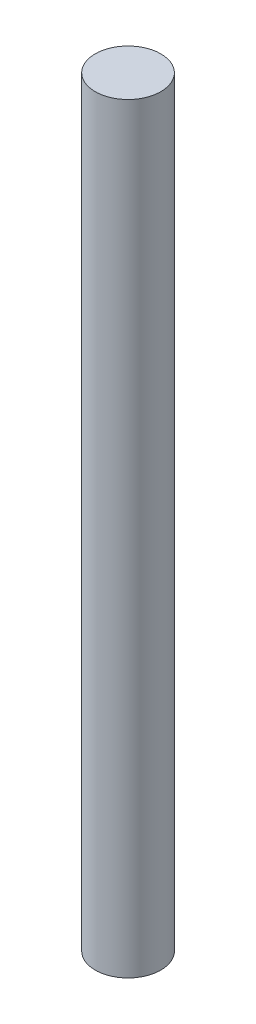
SolidWorks part; units mm, degrees
ref_plane "Front Plane" through (0, 0, 0) normal (0, 0, 1) x (1, 0, 0)
ref_plane "Top Plane" through (0, 0, 0) normal (0, 1, 0) x (1, 0, 0)
ref_plane "Right Plane" through (0, 0, 0) normal (1, 0, 0) x (0, 0, -1)
sketch "Sketch1" plane through (0, 0, 0) normal (0, 1, 0) x (1, 0, 0)
  circle A0 centre (0, 0) radius 2.5
  dimension "D1" = 5
extrude "Boss-Extrude1" add sketch "Sketch1" along normal blind 58
